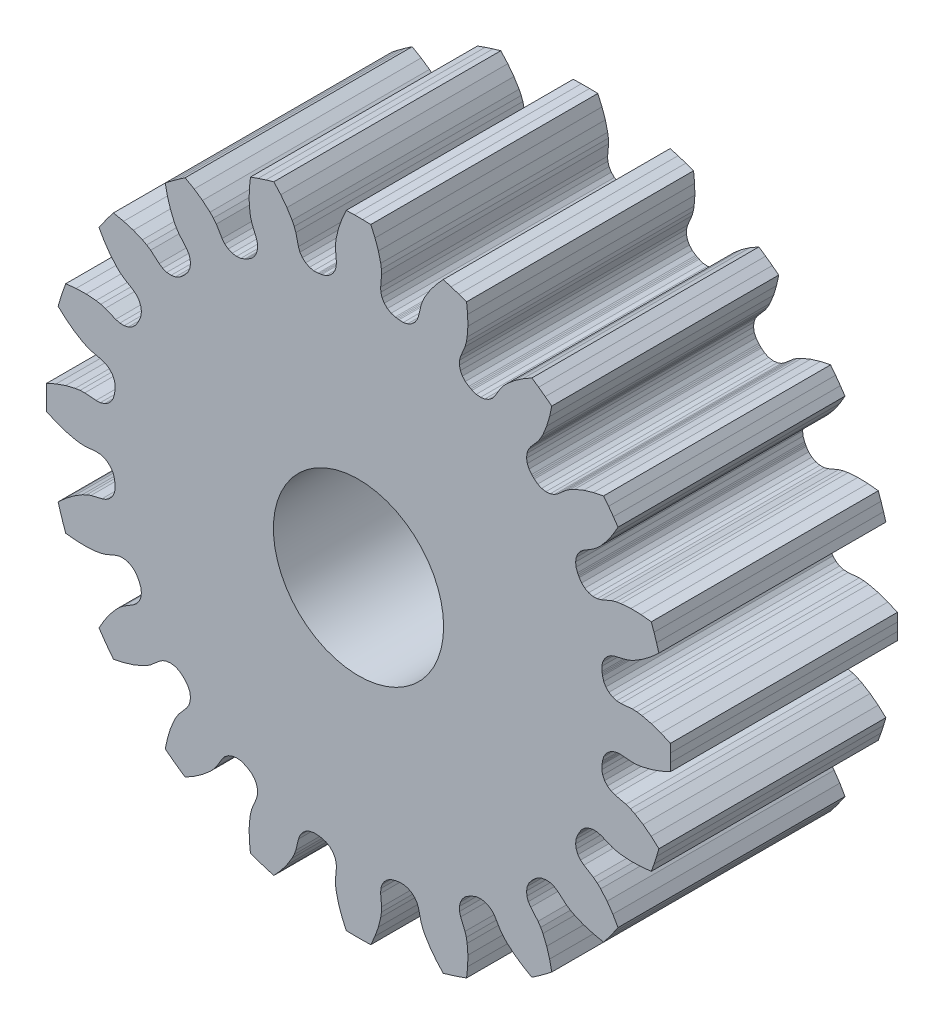
SolidWorks part; units mm, degrees
material "ABS"
ref_plane "Спереди" through (0, 0, 0) normal (0, 0, 1) x (1, 0, 0)
ref_plane "Сверху" through (0, 0, 0) normal (0, 1, 0) x (1, 0, 0)
ref_plane "Справа" through (0, 0, 0) normal (1, 0, 0) x (0, 0, -1)
ref_plane "Плоскость1" through (0, 0, 4) normal (0, 0, 1) x (1, 0, 0)
sketch "Эскиз1" plane through (0, 0, 4) normal (0, 0, 1) x (1, 0, 0)
  line L0 (1.1137, -1.1137) -> (0.982, -1.2314)
  line L1 (0.982, -1.2314) -> (0.838, -1.3336)
  line L2 (0.838, -1.3336) -> (0.6834, -1.419)
  line L3 (0.6834, -1.419) -> (0.5202, -1.4866)
  line L4 (0.5202, -1.4866) -> (0.3505, -1.5355)
  line L5 (0.3505, -1.5355) -> (0.1763, -1.5651)
  line L6 (0.1763, -1.5651) -> (0, -1.575)
  line L7 (0, -1.575) -> (-0.1763, -1.5651)
  line L8 (-0.1763, -1.5651) -> (-0.3505, -1.5355)
  line L9 (-0.3505, -1.5355) -> (-0.5202, -1.4866)
  line L10 (-0.5202, -1.4866) -> (-0.6834, -1.419)
  line L11 (-0.6834, -1.419) -> (-0.838, -1.3336)
  line L12 (-0.838, -1.3336) -> (-0.982, -1.2314)
  line L13 (-0.982, -1.2314) -> (-1.1137, -1.1137)
  line L14 (-1.1137, -1.1137) -> (-1.2314, -0.982)
  line L15 (-1.2314, -0.982) -> (-1.3336, -0.838)
  line L16 (-1.3336, -0.838) -> (-1.419, -0.6834)
  line L17 (-1.419, -0.6834) -> (-1.4866, -0.5202)
  line L18 (-1.4866, -0.5202) -> (-1.5355, -0.3505)
  line L19 (-1.5355, -0.3505) -> (-1.5651, -0.1763)
  line L20 (-1.5651, -0.1763) -> (-1.575, 0)
  line L21 (-1.575, 0) -> (-1.5651, 0.1763)
  line L22 (-1.5651, 0.1763) -> (-1.5355, 0.3505)
  line L23 (-1.5355, 0.3505) -> (-1.4866, 0.5202)
  line L24 (-1.4866, 0.5202) -> (-1.419, 0.6834)
  line L25 (-1.419, 0.6834) -> (-1.3336, 0.838)
  line L26 (-1.3336, 0.838) -> (-1.2314, 0.982)
  line L27 (-1.2314, 0.982) -> (-1.1137, 1.1137)
  line L28 (-1.1137, 1.1137) -> (-0.982, 1.2314)
  line L29 (-0.982, 1.2314) -> (-0.838, 1.3336)
  line L30 (-0.838, 1.3336) -> (-0.6834, 1.419)
  line L31 (-0.6834, 1.419) -> (-0.5202, 1.4866)
  line L32 (-0.5202, 1.4866) -> (-0.3505, 1.5355)
  line L33 (-0.3505, 1.5355) -> (-0.1763, 1.5651)
  line L34 (-0.1763, 1.5651) -> (0, 1.575)
  line L35 (0, 1.575) -> (0.1763, 1.5651)
  line L36 (0.1763, 1.5651) -> (0.3505, 1.5355)
  line L37 (0.3505, 1.5355) -> (0.5202, 1.4866)
  line L38 (0.5202, 1.4866) -> (0.6834, 1.419)
  line L39 (0.6834, 1.419) -> (0.838, 1.3336)
  line L40 (0.838, 1.3336) -> (0.982, 1.2314)
  line L41 (0.982, 1.2314) -> (1.1137, 1.1137)
  line L42 (1.1137, 1.1137) -> (1.2314, 0.982)
  line L43 (1.2314, 0.982) -> (1.3336, 0.838)
  line L44 (1.3336, 0.838) -> (1.419, 0.6834)
  line L45 (1.419, 0.6834) -> (1.4866, 0.5202)
  line L46 (1.4866, 0.5202) -> (1.5355, 0.3505)
  line L47 (1.5355, 0.3505) -> (1.5651, 0.1763)
  line L48 (1.5651, 0.1763) -> (1.575, 0)
  line L49 (1.575, 0) -> (1.5651, -0.1763)
  line L50 (1.5651, -0.1763) -> (1.5355, -0.3505)
  line L51 (1.5355, -0.3505) -> (1.4866, -0.5202)
  line L52 (1.4866, -0.5202) -> (1.419, -0.6834)
  line L53 (1.419, -0.6834) -> (1.3336, -0.838)
  line L54 (1.3336, -0.838) -> (1.2314, -0.982)
  line L55 (1.2314, -0.982) -> (1.1137, -1.1137)
  line L56 (4.3213, -0.5748) -> (4.3594, -0.5091)
  line L57 (4.3594, -0.5091) -> (4.4126, -0.4548)
  line L58 (4.4126, -0.4548) -> (4.4776, -0.4155)
  line L59 (4.4776, -0.4155) -> (4.5504, -0.3935)
  line L60 (4.5504, -0.3935) -> (4.6263, -0.3903)
  line L61 (4.6263, -0.3903) -> (4.8236, -0.4066)
  line L62 (4.8236, -0.4066) -> (4.9072, -0.4032)
  line L63 (4.9072, -0.4032) -> (4.9912, -0.3911)
  line L64 (4.9912, -0.3911) -> (5.1598, -0.35)
  line L65 (5.1598, -0.35) -> (5.3282, -0.2909)
  line L66 (5.3282, -0.2909) -> (5.4957, -0.2164)
  line L67 (5.4957, -0.2164) -> (5.4995, -0.0722)
  line L68 (5.4995, -0.0722) -> (5.4995, 0.0722)
  line L69 (5.4995, 0.0722) -> (5.4957, 0.2164)
  line L70 (5.4957, 0.2164) -> (5.3282, 0.2909)
  line L71 (5.3282, 0.2909) -> (5.1598, 0.35)
  line L72 (5.1598, 0.35) -> (4.9912, 0.3911)
  line L73 (4.9912, 0.3911) -> (4.9072, 0.4032)
  line L74 (4.9072, 0.4032) -> (4.8236, 0.4066)
  line L75 (4.8236, 0.4066) -> (4.6263, 0.3903)
  line L76 (4.6263, 0.3903) -> (4.5504, 0.3935)
  line L77 (4.5504, 0.3935) -> (4.4776, 0.4155)
  line L78 (4.4776, 0.4155) -> (4.4126, 0.4548)
  line L79 (4.4126, 0.4548) -> (4.3594, 0.5091)
  line L80 (4.3594, 0.5091) -> (4.3213, 0.5748)
  line L81 (4.3213, 0.5748) -> (4.3007, 0.6479)
  line L82 (4.3007, 0.6479) -> (4.2974, 0.6696)
  line L83 (4.2974, 0.6696) -> (4.2939, 0.6912)
  line L84 (4.2939, 0.6912) -> (4.2904, 0.7128)
  line L85 (4.2904, 0.7128) -> (4.2874, 0.7887)
  line L86 (4.2874, 0.7887) -> (4.3033, 0.863)
  line L87 (4.3033, 0.863) -> (4.3372, 0.931)
  line L88 (4.3372, 0.931) -> (4.3869, 0.9885)
  line L89 (4.3869, 0.9885) -> (4.4493, 1.0319)
  line L90 (4.4493, 1.0319) -> (4.5205, 1.0585)
  line L91 (4.5205, 1.0585) -> (4.7132, 1.1039)
  line L92 (4.7132, 1.1039) -> (4.7916, 1.133)
  line L93 (4.7916, 1.133) -> (4.8678, 1.1704)
  line L94 (4.8678, 1.1704) -> (5.0154, 1.2616)
  line L95 (5.0154, 1.2616) -> (5.1573, 1.3698)
  line L96 (5.1573, 1.3698) -> (5.2936, 1.4925)
  line L97 (5.2936, 1.4925) -> (5.2527, 1.6308)
  line L98 (5.2527, 1.6308) -> (5.2081, 1.7681)
  line L99 (5.2081, 1.7681) -> (5.1599, 1.9041)
  line L100 (5.1599, 1.9041) -> (4.9775, 1.9232)
  line L101 (4.9775, 1.9232) -> (4.7991, 1.9273)
  line L102 (4.7991, 1.9273) -> (4.6261, 1.9143)
  line L103 (4.6261, 1.9143) -> (4.5424, 1.8998)
  line L104 (4.5424, 1.8998) -> (4.4619, 1.8772)
  line L105 (4.4619, 1.8772) -> (4.2793, 1.8008)
  line L106 (4.2793, 1.8008) -> (4.2061, 1.7804)
  line L107 (4.2061, 1.7804) -> (4.1301, 1.7788)
  line L108 (4.1301, 1.7788) -> (4.0561, 1.7961)
  line L109 (4.0561, 1.7961) -> (3.9887, 1.8313)
  line L110 (3.9887, 1.8313) -> (3.9322, 1.882)
  line L111 (3.9322, 1.882) -> (3.89, 1.9452)
  line L112 (3.89, 1.9452) -> (3.8801, 1.9647)
  line L113 (3.8801, 1.9647) -> (3.8702, 1.9842)
  line L114 (3.8702, 1.9842) -> (3.8602, 2.0037)
  line L115 (3.8602, 2.0037) -> (3.8339, 2.075)
  line L116 (3.8339, 2.075) -> (3.826, 2.1506)
  line L117 (3.826, 2.1506) -> (3.8372, 2.2257)
  line L118 (3.8372, 2.2257) -> (3.8667, 2.2958)
  line L119 (3.8667, 2.2958) -> (3.9126, 2.3563)
  line L120 (3.9126, 2.3563) -> (3.9721, 2.4036)
  line L121 (3.9721, 2.4036) -> (4.1414, 2.5064)
  line L122 (4.1414, 2.5064) -> (4.207, 2.5582)
  line L123 (4.207, 2.5582) -> (4.2679, 2.6174)
  line L124 (4.2679, 2.6174) -> (4.3801, 2.7497)
  line L125 (4.3801, 2.7497) -> (4.4816, 2.8965)
  line L126 (4.4816, 2.8965) -> (4.5734, 3.0552)
  line L127 (4.5734, 3.0552) -> (4.4916, 3.1742)
  line L128 (4.4916, 3.1742) -> (4.4068, 3.2909)
  line L129 (4.4068, 3.2909) -> (4.3189, 3.4054)
  line L130 (4.3189, 3.4054) -> (4.1396, 3.3672)
  line L131 (4.1396, 3.3672) -> (3.9686, 3.316)
  line L132 (3.9686, 3.316) -> (3.8081, 3.2502)
  line L133 (3.8081, 3.2502) -> (3.733, 3.2105)
  line L134 (3.733, 3.2105) -> (3.6634, 3.1642)
  line L135 (3.6634, 3.1642) -> (3.5134, 3.035)
  line L136 (3.5134, 3.035) -> (3.45, 2.993)
  line L137 (3.45, 2.993) -> (3.3783, 2.968)
  line L138 (3.3783, 2.968) -> (3.3026, 2.9616)
  line L139 (3.3026, 2.9616) -> (3.2276, 2.9742)
  line L140 (3.2276, 2.9742) -> (3.1581, 3.005)
  line L141 (3.1581, 3.005) -> (3.0985, 3.0521)
  line L142 (3.0985, 3.0521) -> (3.0831, 3.0676)
  line L143 (3.0831, 3.0676) -> (3.0676, 3.0831)
  line L144 (3.0676, 3.0831) -> (3.0521, 3.0985)
  line L145 (3.0521, 3.0985) -> (3.005, 3.1581)
  line L146 (3.005, 3.1581) -> (2.9742, 3.2276)
  line L147 (2.9742, 3.2276) -> (2.9616, 3.3026)
  line L148 (2.9616, 3.3026) -> (2.968, 3.3783)
  line L149 (2.968, 3.3783) -> (2.993, 3.45)
  line L150 (2.993, 3.45) -> (3.035, 3.5134)
  line L151 (3.035, 3.5134) -> (3.1642, 3.6634)
  line L152 (3.1642, 3.6634) -> (3.2105, 3.733)
  line L153 (3.2105, 3.733) -> (3.2502, 3.8081)
  line L154 (3.2502, 3.8081) -> (3.316, 3.9686)
  line L155 (3.316, 3.9686) -> (3.3672, 4.1396)
  line L156 (3.3672, 4.1396) -> (3.4054, 4.3189)
  line L157 (3.4054, 4.3189) -> (3.2909, 4.4068)
  line L158 (3.2909, 4.4068) -> (3.1742, 4.4916)
  line L159 (3.1742, 4.4916) -> (3.0552, 4.5734)
  line L160 (3.0552, 4.5734) -> (2.8965, 4.4816)
  line L161 (2.8965, 4.4816) -> (2.7497, 4.3801)
  line L162 (2.7497, 4.3801) -> (2.6174, 4.2679)
  line L163 (2.6174, 4.2679) -> (2.5582, 4.207)
  line L164 (2.5582, 4.207) -> (2.5064, 4.1414)
  line L165 (2.5064, 4.1414) -> (2.4036, 3.9721)
  line L166 (2.4036, 3.9721) -> (2.3563, 3.9126)
  line L167 (2.3563, 3.9126) -> (2.2958, 3.8667)
  line L168 (2.2958, 3.8667) -> (2.2257, 3.8372)
  line L169 (2.2257, 3.8372) -> (2.1506, 3.826)
  line L170 (2.1506, 3.826) -> (2.075, 3.8339)
  line L171 (2.075, 3.8339) -> (2.0037, 3.8602)
  line L172 (2.0037, 3.8602) -> (1.9842, 3.8702)
  line L173 (1.9842, 3.8702) -> (1.9647, 3.8801)
  line L174 (1.9647, 3.8801) -> (1.9452, 3.89)
  line L175 (1.9452, 3.89) -> (1.882, 3.9322)
  line L176 (1.882, 3.9322) -> (1.8313, 3.9887)
  line L177 (1.8313, 3.9887) -> (1.7961, 4.0561)
  line L178 (1.7961, 4.0561) -> (1.7788, 4.1301)
  line L179 (1.7788, 4.1301) -> (1.7804, 4.2061)
  line L180 (1.7804, 4.2061) -> (1.8008, 4.2793)
  line L181 (1.8008, 4.2793) -> (1.8772, 4.4619)
  line L182 (1.8772, 4.4619) -> (1.8998, 4.5424)
  line L183 (1.8998, 4.5424) -> (1.9143, 4.6261)
  line L184 (1.9143, 4.6261) -> (1.9273, 4.7991)
  line L185 (1.9273, 4.7991) -> (1.9232, 4.9775)
  line L186 (1.9232, 4.9775) -> (1.9041, 5.1599)
  line L187 (1.9041, 5.1599) -> (1.7681, 5.2081)
  line L188 (1.7681, 5.2081) -> (1.6308, 5.2527)
  line L189 (1.6308, 5.2527) -> (1.4925, 5.2936)
  line L190 (1.4925, 5.2936) -> (1.3698, 5.1573)
  line L191 (1.3698, 5.1573) -> (1.2616, 5.0154)
  line L192 (1.2616, 5.0154) -> (1.1704, 4.8678)
  line L193 (1.1704, 4.8678) -> (1.133, 4.7916)
  line L194 (1.133, 4.7916) -> (1.1039, 4.7132)
  line L195 (1.1039, 4.7132) -> (1.0585, 4.5205)
  line L196 (1.0585, 4.5205) -> (1.0319, 4.4493)
  line L197 (1.0319, 4.4493) -> (0.9885, 4.3869)
  line L198 (0.9885, 4.3869) -> (0.931, 4.3372)
  line L199 (0.931, 4.3372) -> (0.863, 4.3033)
  line L200 (0.863, 4.3033) -> (0.7887, 4.2874)
  line L201 (0.7887, 4.2874) -> (0.7128, 4.2904)
  line L202 (0.7128, 4.2904) -> (0.6912, 4.2939)
  line L203 (0.6912, 4.2939) -> (0.6696, 4.2974)
  line L204 (0.6696, 4.2974) -> (0.6479, 4.3007)
  line L205 (0.6479, 4.3007) -> (0.5748, 4.3213)
  line L206 (0.5748, 4.3213) -> (0.5091, 4.3594)
  line L207 (0.5091, 4.3594) -> (0.4548, 4.4126)
  line L208 (0.4548, 4.4126) -> (0.4155, 4.4776)
  line L209 (0.4155, 4.4776) -> (0.3935, 4.5504)
  line L210 (0.3935, 4.5504) -> (0.3903, 4.6263)
  line L211 (0.3903, 4.6263) -> (0.4066, 4.8236)
  line L212 (0.4066, 4.8236) -> (0.4032, 4.9072)
  line L213 (0.4032, 4.9072) -> (0.3911, 4.9912)
  line L214 (0.3911, 4.9912) -> (0.35, 5.1598)
  line L215 (0.35, 5.1598) -> (0.2909, 5.3282)
  line L216 (0.2909, 5.3282) -> (0.2164, 5.4957)
  line L217 (0.2164, 5.4957) -> (0.0722, 5.4995)
  line L218 (0.0722, 5.4995) -> (-0.0722, 5.4995)
  line L219 (-0.0722, 5.4995) -> (-0.2164, 5.4957)
  line L220 (-0.2164, 5.4957) -> (-0.2909, 5.3282)
  line L221 (-0.2909, 5.3282) -> (-0.35, 5.1598)
  line L222 (-0.35, 5.1598) -> (-0.3911, 4.9912)
  line L223 (-0.3911, 4.9912) -> (-0.4032, 4.9072)
  line L224 (-0.4032, 4.9072) -> (-0.4066, 4.8236)
  line L225 (-0.4066, 4.8236) -> (-0.3903, 4.6263)
  line L226 (-0.3903, 4.6263) -> (-0.3935, 4.5504)
  line L227 (-0.3935, 4.5504) -> (-0.4155, 4.4776)
  line L228 (-0.4155, 4.4776) -> (-0.4548, 4.4126)
  line L229 (-0.4548, 4.4126) -> (-0.5091, 4.3594)
  line L230 (-0.5091, 4.3594) -> (-0.5748, 4.3213)
  line L231 (-0.5748, 4.3213) -> (-0.6479, 4.3007)
  line L232 (-0.6479, 4.3007) -> (-0.6696, 4.2974)
  line L233 (-0.6696, 4.2974) -> (-0.6912, 4.2939)
  line L234 (-0.6912, 4.2939) -> (-0.7128, 4.2904)
  line L235 (-0.7128, 4.2904) -> (-0.7887, 4.2874)
  line L236 (-0.7887, 4.2874) -> (-0.863, 4.3033)
  line L237 (-0.863, 4.3033) -> (-0.931, 4.3372)
  line L238 (-0.931, 4.3372) -> (-0.9885, 4.3869)
  line L239 (-0.9885, 4.3869) -> (-1.0319, 4.4493)
  line L240 (-1.0319, 4.4493) -> (-1.0585, 4.5205)
  line L241 (-1.0585, 4.5205) -> (-1.1039, 4.7132)
  line L242 (-1.1039, 4.7132) -> (-1.133, 4.7916)
  line L243 (-1.133, 4.7916) -> (-1.1704, 4.8678)
  line L244 (-1.1704, 4.8678) -> (-1.2616, 5.0154)
  line L245 (-1.2616, 5.0154) -> (-1.3698, 5.1573)
  line L246 (-1.3698, 5.1573) -> (-1.4925, 5.2936)
  line L247 (-1.4925, 5.2936) -> (-1.6308, 5.2527)
  line L248 (-1.6308, 5.2527) -> (-1.7681, 5.2081)
  line L249 (-1.7681, 5.2081) -> (-1.9041, 5.1599)
  line L250 (-1.9041, 5.1599) -> (-1.9232, 4.9775)
  line L251 (-1.9232, 4.9775) -> (-1.9273, 4.7991)
  line L252 (-1.9273, 4.7991) -> (-1.9143, 4.6261)
  line L253 (-1.9143, 4.6261) -> (-1.8998, 4.5424)
  line L254 (-1.8998, 4.5424) -> (-1.8772, 4.4619)
  line L255 (-1.8772, 4.4619) -> (-1.8008, 4.2793)
  line L256 (-1.8008, 4.2793) -> (-1.7804, 4.2061)
  line L257 (-1.7804, 4.2061) -> (-1.7788, 4.1301)
  line L258 (-1.7788, 4.1301) -> (-1.7961, 4.0561)
  line L259 (-1.7961, 4.0561) -> (-1.8313, 3.9887)
  line L260 (-1.8313, 3.9887) -> (-1.882, 3.9322)
  line L261 (-1.882, 3.9322) -> (-1.9452, 3.89)
  line L262 (-1.9452, 3.89) -> (-1.9647, 3.8801)
  line L263 (-1.9647, 3.8801) -> (-1.9842, 3.8702)
  line L264 (-1.9842, 3.8702) -> (-2.0037, 3.8602)
  line L265 (-2.0037, 3.8602) -> (-2.075, 3.8339)
  line L266 (-2.075, 3.8339) -> (-2.1506, 3.826)
  line L267 (-2.1506, 3.826) -> (-2.2257, 3.8372)
  line L268 (-2.2257, 3.8372) -> (-2.2958, 3.8667)
  line L269 (-2.2958, 3.8667) -> (-2.3563, 3.9126)
  line L270 (-2.3563, 3.9126) -> (-2.4036, 3.9721)
  line L271 (-2.4036, 3.9721) -> (-2.5064, 4.1414)
  line L272 (-2.5064, 4.1414) -> (-2.5582, 4.207)
  line L273 (-2.5582, 4.207) -> (-2.6174, 4.2679)
  line L274 (-2.6174, 4.2679) -> (-2.7497, 4.3801)
  line L275 (-2.7497, 4.3801) -> (-2.8965, 4.4816)
  line L276 (-2.8965, 4.4816) -> (-3.0552, 4.5734)
  line L277 (-3.0552, 4.5734) -> (-3.1742, 4.4916)
  line L278 (-3.1742, 4.4916) -> (-3.2909, 4.4068)
  line L279 (-3.2909, 4.4068) -> (-3.4054, 4.3189)
  line L280 (-3.4054, 4.3189) -> (-3.3672, 4.1396)
  line L281 (-3.3672, 4.1396) -> (-3.316, 3.9686)
  line L282 (-3.316, 3.9686) -> (-3.2502, 3.8081)
  line L283 (-3.2502, 3.8081) -> (-3.2105, 3.733)
  line L284 (-3.2105, 3.733) -> (-3.1642, 3.6634)
  line L285 (-3.1642, 3.6634) -> (-3.035, 3.5134)
  line L286 (-3.035, 3.5134) -> (-2.993, 3.45)
  line L287 (-2.993, 3.45) -> (-2.968, 3.3783)
  line L288 (-2.968, 3.3783) -> (-2.9616, 3.3026)
  line L289 (-2.9616, 3.3026) -> (-2.9742, 3.2276)
  line L290 (-2.9742, 3.2276) -> (-3.005, 3.1581)
  line L291 (-3.005, 3.1581) -> (-3.0521, 3.0985)
  line L292 (-3.0521, 3.0985) -> (-3.0676, 3.0831)
  line L293 (-3.0676, 3.0831) -> (-3.0831, 3.0676)
  line L294 (-3.0831, 3.0676) -> (-3.0985, 3.0521)
  line L295 (-3.0985, 3.0521) -> (-3.1581, 3.005)
  line L296 (-3.1581, 3.005) -> (-3.2276, 2.9742)
  line L297 (-3.2276, 2.9742) -> (-3.3026, 2.9616)
  line L298 (-3.3026, 2.9616) -> (-3.3783, 2.968)
  line L299 (-3.3783, 2.968) -> (-3.45, 2.993)
  line L300 (-3.45, 2.993) -> (-3.5134, 3.035)
  line L301 (-3.5134, 3.035) -> (-3.6634, 3.1642)
  line L302 (-3.6634, 3.1642) -> (-3.733, 3.2105)
  line L303 (-3.733, 3.2105) -> (-3.8081, 3.2502)
  line L304 (-3.8081, 3.2502) -> (-3.9686, 3.316)
  line L305 (-3.9686, 3.316) -> (-4.1396, 3.3672)
  line L306 (-4.1396, 3.3672) -> (-4.3189, 3.4054)
  line L307 (-4.3189, 3.4054) -> (-4.4068, 3.2909)
  line L308 (-4.4068, 3.2909) -> (-4.4916, 3.1742)
  line L309 (-4.4916, 3.1742) -> (-4.5734, 3.0552)
  line L310 (-4.5734, 3.0552) -> (-4.4816, 2.8965)
  line L311 (-4.4816, 2.8965) -> (-4.3801, 2.7497)
  line L312 (-4.3801, 2.7497) -> (-4.2679, 2.6174)
  line L313 (-4.2679, 2.6174) -> (-4.207, 2.5582)
  line L314 (-4.207, 2.5582) -> (-4.1414, 2.5064)
  line L315 (-4.1414, 2.5064) -> (-3.9721, 2.4036)
  line L316 (-3.9721, 2.4036) -> (-3.9126, 2.3563)
  line L317 (-3.9126, 2.3563) -> (-3.8667, 2.2958)
  line L318 (-3.8667, 2.2958) -> (-3.8372, 2.2257)
  line L319 (-3.8372, 2.2257) -> (-3.826, 2.1506)
  line L320 (-3.826, 2.1506) -> (-3.8339, 2.075)
  line L321 (-3.8339, 2.075) -> (-3.8602, 2.0037)
  line L322 (-3.8602, 2.0037) -> (-3.8702, 1.9842)
  line L323 (-3.8702, 1.9842) -> (-3.8801, 1.9647)
  line L324 (-3.8801, 1.9647) -> (-3.89, 1.9452)
  line L325 (-3.89, 1.9452) -> (-3.9322, 1.882)
  line L326 (-3.9322, 1.882) -> (-3.9887, 1.8313)
  line L327 (-3.9887, 1.8313) -> (-4.0561, 1.7961)
  line L328 (-4.0561, 1.7961) -> (-4.1301, 1.7788)
  line L329 (-4.1301, 1.7788) -> (-4.2061, 1.7804)
  line L330 (-4.2061, 1.7804) -> (-4.2793, 1.8008)
  line L331 (-4.2793, 1.8008) -> (-4.4619, 1.8772)
  line L332 (-4.4619, 1.8772) -> (-4.5424, 1.8998)
  line L333 (-4.5424, 1.8998) -> (-4.6261, 1.9143)
  line L334 (-4.6261, 1.9143) -> (-4.7991, 1.9273)
  line L335 (-4.7991, 1.9273) -> (-4.9775, 1.9232)
  line L336 (-4.9775, 1.9232) -> (-5.1599, 1.9041)
  line L337 (-5.1599, 1.9041) -> (-5.2081, 1.7681)
  line L338 (-5.2081, 1.7681) -> (-5.2527, 1.6308)
  line L339 (-5.2527, 1.6308) -> (-5.2936, 1.4925)
  line L340 (-5.2936, 1.4925) -> (-5.1573, 1.3698)
  line L341 (-5.1573, 1.3698) -> (-5.0154, 1.2616)
  line L342 (-5.0154, 1.2616) -> (-4.8678, 1.1704)
  line L343 (-4.8678, 1.1704) -> (-4.7916, 1.133)
  line L344 (-4.7916, 1.133) -> (-4.7132, 1.1039)
  line L345 (-4.7132, 1.1039) -> (-4.5205, 1.0585)
  line L346 (-4.5205, 1.0585) -> (-4.4493, 1.0319)
  line L347 (-4.4493, 1.0319) -> (-4.3869, 0.9885)
  line L348 (-4.3869, 0.9885) -> (-4.3372, 0.931)
  line L349 (-4.3372, 0.931) -> (-4.3033, 0.863)
  line L350 (-4.3033, 0.863) -> (-4.2874, 0.7887)
  line L351 (-4.2874, 0.7887) -> (-4.2904, 0.7128)
  line L352 (-4.2904, 0.7128) -> (-4.2939, 0.6912)
  line L353 (-4.2939, 0.6912) -> (-4.2974, 0.6696)
  line L354 (-4.2974, 0.6696) -> (-4.3007, 0.6479)
  line L355 (-4.3007, 0.6479) -> (-4.3213, 0.5748)
  line L356 (-4.3213, 0.5748) -> (-4.3594, 0.5091)
  line L357 (-4.3594, 0.5091) -> (-4.4126, 0.4548)
  line L358 (-4.4126, 0.4548) -> (-4.4776, 0.4155)
  line L359 (-4.4776, 0.4155) -> (-4.5504, 0.3935)
  line L360 (-4.5504, 0.3935) -> (-4.6263, 0.3903)
  line L361 (-4.6263, 0.3903) -> (-4.8236, 0.4066)
  line L362 (-4.8236, 0.4066) -> (-4.9072, 0.4032)
  line L363 (-4.9072, 0.4032) -> (-4.9912, 0.3911)
  line L364 (-4.9912, 0.3911) -> (-5.1598, 0.35)
  line L365 (-5.1598, 0.35) -> (-5.3282, 0.2909)
  line L366 (-5.3282, 0.2909) -> (-5.4957, 0.2164)
  line L367 (-5.4957, 0.2164) -> (-5.4995, 0.0722)
  line L368 (-5.4995, 0.0722) -> (-5.4995, -0.0722)
  line L369 (-5.4995, -0.0722) -> (-5.4957, -0.2164)
  line L370 (-5.4957, -0.2164) -> (-5.3282, -0.2909)
  line L371 (-5.3282, -0.2909) -> (-5.1598, -0.35)
  line L372 (-5.1598, -0.35) -> (-4.9912, -0.3911)
  line L373 (-4.9912, -0.3911) -> (-4.9072, -0.4032)
  line L374 (-4.9072, -0.4032) -> (-4.8236, -0.4066)
  line L375 (-4.8236, -0.4066) -> (-4.6263, -0.3903)
  line L376 (-4.6263, -0.3903) -> (-4.5504, -0.3935)
  line L377 (-4.5504, -0.3935) -> (-4.4776, -0.4155)
  line L378 (-4.4776, -0.4155) -> (-4.4126, -0.4548)
  line L379 (-4.4126, -0.4548) -> (-4.3594, -0.5091)
  line L380 (-4.3594, -0.5091) -> (-4.3213, -0.5748)
  line L381 (-4.3213, -0.5748) -> (-4.3007, -0.6479)
  line L382 (-4.3007, -0.6479) -> (-4.2974, -0.6696)
  line L383 (-4.2974, -0.6696) -> (-4.2939, -0.6912)
  line L384 (-4.2939, -0.6912) -> (-4.2904, -0.7128)
  line L385 (-4.2904, -0.7128) -> (-4.2874, -0.7887)
  line L386 (-4.2874, -0.7887) -> (-4.3033, -0.863)
  line L387 (-4.3033, -0.863) -> (-4.3372, -0.931)
  line L388 (-4.3372, -0.931) -> (-4.3869, -0.9885)
  line L389 (-4.3869, -0.9885) -> (-4.4493, -1.0319)
  line L390 (-4.4493, -1.0319) -> (-4.5205, -1.0585)
  line L391 (-4.5205, -1.0585) -> (-4.7132, -1.1039)
  line L392 (-4.7132, -1.1039) -> (-4.7916, -1.133)
  line L393 (-4.7916, -1.133) -> (-4.8678, -1.1704)
  line L394 (-4.8678, -1.1704) -> (-5.0154, -1.2616)
  line L395 (-5.0154, -1.2616) -> (-5.1573, -1.3698)
  line L396 (-5.1573, -1.3698) -> (-5.2936, -1.4925)
  line L397 (-5.2936, -1.4925) -> (-5.2527, -1.6308)
  line L398 (-5.2527, -1.6308) -> (-5.2081, -1.7681)
  line L399 (-5.2081, -1.7681) -> (-5.1599, -1.9041)
  line L400 (-5.1599, -1.9041) -> (-4.9775, -1.9232)
  line L401 (-4.9775, -1.9232) -> (-4.7991, -1.9273)
  line L402 (-4.7991, -1.9273) -> (-4.6261, -1.9143)
  line L403 (-4.6261, -1.9143) -> (-4.5424, -1.8998)
  line L404 (-4.5424, -1.8998) -> (-4.4619, -1.8772)
  line L405 (-4.4619, -1.8772) -> (-4.2793, -1.8008)
  line L406 (-4.2793, -1.8008) -> (-4.2061, -1.7804)
  line L407 (-4.2061, -1.7804) -> (-4.1301, -1.7788)
  line L408 (-4.1301, -1.7788) -> (-4.0561, -1.7961)
  line L409 (-4.0561, -1.7961) -> (-3.9887, -1.8313)
  line L410 (-3.9887, -1.8313) -> (-3.9322, -1.882)
  line L411 (-3.9322, -1.882) -> (-3.89, -1.9452)
  line L412 (-3.89, -1.9452) -> (-3.8801, -1.9647)
  line L413 (-3.8801, -1.9647) -> (-3.8702, -1.9842)
  line L414 (-3.8702, -1.9842) -> (-3.8602, -2.0037)
  line L415 (-3.8602, -2.0037) -> (-3.8339, -2.075)
  line L416 (-3.8339, -2.075) -> (-3.826, -2.1506)
  line L417 (-3.826, -2.1506) -> (-3.8372, -2.2257)
  line L418 (-3.8372, -2.2257) -> (-3.8667, -2.2958)
  line L419 (-3.8667, -2.2958) -> (-3.9126, -2.3563)
  line L420 (-3.9126, -2.3563) -> (-3.9721, -2.4036)
  line L421 (-3.9721, -2.4036) -> (-4.1414, -2.5064)
  line L422 (-4.1414, -2.5064) -> (-4.207, -2.5582)
  line L423 (-4.207, -2.5582) -> (-4.2679, -2.6174)
  line L424 (-4.2679, -2.6174) -> (-4.3801, -2.7497)
  line L425 (-4.3801, -2.7497) -> (-4.4816, -2.8965)
  line L426 (-4.4816, -2.8965) -> (-4.5734, -3.0552)
  line L427 (-4.5734, -3.0552) -> (-4.4916, -3.1742)
  line L428 (-4.4916, -3.1742) -> (-4.4068, -3.2909)
  line L429 (-4.4068, -3.2909) -> (-4.3189, -3.4054)
  line L430 (-4.3189, -3.4054) -> (-4.1396, -3.3672)
  line L431 (-4.1396, -3.3672) -> (-3.9686, -3.316)
  line L432 (-3.9686, -3.316) -> (-3.8081, -3.2502)
  line L433 (-3.8081, -3.2502) -> (-3.733, -3.2105)
  line L434 (-3.733, -3.2105) -> (-3.6634, -3.1642)
  line L435 (-3.6634, -3.1642) -> (-3.5134, -3.035)
  line L436 (-3.5134, -3.035) -> (-3.45, -2.993)
  line L437 (-3.45, -2.993) -> (-3.3783, -2.968)
  line L438 (-3.3783, -2.968) -> (-3.3026, -2.9616)
  line L439 (-3.3026, -2.9616) -> (-3.2276, -2.9742)
  line L440 (-3.2276, -2.9742) -> (-3.1581, -3.005)
  line L441 (-3.1581, -3.005) -> (-3.0985, -3.0521)
  line L442 (-3.0985, -3.0521) -> (-3.0831, -3.0676)
  line L443 (-3.0831, -3.0676) -> (-3.0676, -3.0831)
  line L444 (-3.0676, -3.0831) -> (-3.0521, -3.0985)
  line L445 (-3.0521, -3.0985) -> (-3.005, -3.1581)
  line L446 (-3.005, -3.1581) -> (-2.9742, -3.2276)
  line L447 (-2.9742, -3.2276) -> (-2.9616, -3.3026)
  line L448 (-2.9616, -3.3026) -> (-2.968, -3.3783)
  line L449 (-2.968, -3.3783) -> (-2.993, -3.45)
  line L450 (-2.993, -3.45) -> (-3.035, -3.5134)
  line L451 (-3.035, -3.5134) -> (-3.1642, -3.6634)
  line L452 (-3.1642, -3.6634) -> (-3.2105, -3.733)
  line L453 (-3.2105, -3.733) -> (-3.2502, -3.8081)
  line L454 (-3.2502, -3.8081) -> (-3.316, -3.9686)
  line L455 (-3.316, -3.9686) -> (-3.3672, -4.1396)
  line L456 (-3.3672, -4.1396) -> (-3.4054, -4.3189)
  line L457 (-3.4054, -4.3189) -> (-3.2909, -4.4068)
  line L458 (-3.2909, -4.4068) -> (-3.1742, -4.4916)
  line L459 (-3.1742, -4.4916) -> (-3.0552, -4.5734)
  line L460 (-3.0552, -4.5734) -> (-2.8965, -4.4816)
  line L461 (-2.8965, -4.4816) -> (-2.7497, -4.3801)
  line L462 (-2.7497, -4.3801) -> (-2.6174, -4.2679)
  line L463 (-2.6174, -4.2679) -> (-2.5582, -4.207)
  line L464 (-2.5582, -4.207) -> (-2.5064, -4.1414)
  line L465 (-2.5064, -4.1414) -> (-2.4036, -3.9721)
  line L466 (-2.4036, -3.9721) -> (-2.3563, -3.9126)
  line L467 (-2.3563, -3.9126) -> (-2.2958, -3.8667)
  line L468 (-2.2958, -3.8667) -> (-2.2257, -3.8372)
  line L469 (-2.2257, -3.8372) -> (-2.1506, -3.826)
  line L470 (-2.1506, -3.826) -> (-2.075, -3.8339)
  line L471 (-2.075, -3.8339) -> (-2.0037, -3.8602)
  line L472 (-2.0037, -3.8602) -> (-1.9842, -3.8702)
  line L473 (-1.9842, -3.8702) -> (-1.9647, -3.8801)
  line L474 (-1.9647, -3.8801) -> (-1.9452, -3.89)
  line L475 (-1.9452, -3.89) -> (-1.882, -3.9322)
  line L476 (-1.882, -3.9322) -> (-1.8313, -3.9887)
  line L477 (-1.8313, -3.9887) -> (-1.7961, -4.0561)
  line L478 (-1.7961, -4.0561) -> (-1.7788, -4.1301)
  line L479 (-1.7788, -4.1301) -> (-1.7804, -4.2061)
  line L480 (-1.7804, -4.2061) -> (-1.8008, -4.2793)
  line L481 (-1.8008, -4.2793) -> (-1.8772, -4.4619)
  line L482 (-1.8772, -4.4619) -> (-1.8998, -4.5424)
  line L483 (-1.8998, -4.5424) -> (-1.9143, -4.6261)
  line L484 (-1.9143, -4.6261) -> (-1.9273, -4.7991)
  line L485 (-1.9273, -4.7991) -> (-1.9232, -4.9775)
  line L486 (-1.9232, -4.9775) -> (-1.9041, -5.1599)
  line L487 (-1.9041, -5.1599) -> (-1.7681, -5.2081)
  line L488 (-1.7681, -5.2081) -> (-1.6308, -5.2527)
  line L489 (-1.6308, -5.2527) -> (-1.4925, -5.2936)
  line L490 (-1.4925, -5.2936) -> (-1.3698, -5.1573)
  line L491 (-1.3698, -5.1573) -> (-1.2616, -5.0154)
  line L492 (-1.2616, -5.0154) -> (-1.1704, -4.8678)
  line L493 (-1.1704, -4.8678) -> (-1.133, -4.7916)
  line L494 (-1.133, -4.7916) -> (-1.1039, -4.7132)
  line L495 (-1.1039, -4.7132) -> (-1.0585, -4.5205)
  line L496 (-1.0585, -4.5205) -> (-1.0319, -4.4493)
  line L497 (-1.0319, -4.4493) -> (-0.9885, -4.3869)
  line L498 (-0.9885, -4.3869) -> (-0.931, -4.3372)
  line L499 (-0.931, -4.3372) -> (-0.863, -4.3033)
  line L500 (-0.863, -4.3033) -> (-0.7887, -4.2874)
  line L501 (-0.7887, -4.2874) -> (-0.7128, -4.2904)
  line L502 (-0.7128, -4.2904) -> (-0.6912, -4.2939)
  line L503 (-0.6912, -4.2939) -> (-0.6696, -4.2974)
  line L504 (-0.6696, -4.2974) -> (-0.6479, -4.3007)
  line L505 (-0.6479, -4.3007) -> (-0.5748, -4.3213)
  line L506 (-0.5748, -4.3213) -> (-0.5091, -4.3594)
  line L507 (-0.5091, -4.3594) -> (-0.4548, -4.4126)
  line L508 (-0.4548, -4.4126) -> (-0.4155, -4.4776)
  line L509 (-0.4155, -4.4776) -> (-0.3935, -4.5504)
  line L510 (-0.3935, -4.5504) -> (-0.3903, -4.6263)
  line L511 (-0.3903, -4.6263) -> (-0.4066, -4.8236)
  line L512 (-0.4066, -4.8236) -> (-0.4032, -4.9072)
  line L513 (-0.4032, -4.9072) -> (-0.3911, -4.9912)
  line L514 (-0.3911, -4.9912) -> (-0.35, -5.1598)
  line L515 (-0.35, -5.1598) -> (-0.2909, -5.3282)
  line L516 (-0.2909, -5.3282) -> (-0.2164, -5.4957)
  line L517 (-0.2164, -5.4957) -> (-0.0722, -5.4995)
  line L518 (-0.0722, -5.4995) -> (0.0722, -5.4995)
  line L519 (0.0722, -5.4995) -> (0.2164, -5.4957)
  line L520 (0.2164, -5.4957) -> (0.2909, -5.3282)
  line L521 (0.2909, -5.3282) -> (0.35, -5.1598)
  line L522 (0.35, -5.1598) -> (0.3911, -4.9912)
  line L523 (0.3911, -4.9912) -> (0.4032, -4.9072)
  line L524 (0.4032, -4.9072) -> (0.4066, -4.8236)
  line L525 (0.4066, -4.8236) -> (0.3903, -4.6263)
  line L526 (0.3903, -4.6263) -> (0.3935, -4.5504)
  line L527 (0.3935, -4.5504) -> (0.4155, -4.4776)
  line L528 (0.4155, -4.4776) -> (0.4548, -4.4126)
  line L529 (0.4548, -4.4126) -> (0.5091, -4.3594)
  line L530 (0.5091, -4.3594) -> (0.5748, -4.3213)
  line L531 (0.5748, -4.3213) -> (0.6479, -4.3007)
  line L532 (0.6479, -4.3007) -> (0.6696, -4.2974)
  line L533 (0.6696, -4.2974) -> (0.6912, -4.2939)
  line L534 (0.6912, -4.2939) -> (0.7128, -4.2904)
  line L535 (0.7128, -4.2904) -> (0.7887, -4.2874)
  line L536 (0.7887, -4.2874) -> (0.863, -4.3033)
  line L537 (0.863, -4.3033) -> (0.931, -4.3372)
  line L538 (0.931, -4.3372) -> (0.9885, -4.3869)
  line L539 (0.9885, -4.3869) -> (1.0319, -4.4493)
  line L540 (1.0319, -4.4493) -> (1.0585, -4.5205)
  line L541 (1.0585, -4.5205) -> (1.1039, -4.7132)
  line L542 (1.1039, -4.7132) -> (1.133, -4.7916)
  line L543 (1.133, -4.7916) -> (1.1704, -4.8678)
  line L544 (1.1704, -4.8678) -> (1.2616, -5.0154)
  line L545 (1.2616, -5.0154) -> (1.3698, -5.1573)
  line L546 (1.3698, -5.1573) -> (1.4925, -5.2936)
  line L547 (1.4925, -5.2936) -> (1.6308, -5.2527)
  line L548 (1.6308, -5.2527) -> (1.7681, -5.2081)
  line L549 (1.7681, -5.2081) -> (1.9041, -5.1599)
  line L550 (1.9041, -5.1599) -> (1.9232, -4.9775)
  line L551 (1.9232, -4.9775) -> (1.9273, -4.7991)
  line L552 (1.9273, -4.7991) -> (1.9143, -4.6261)
  line L553 (1.9143, -4.6261) -> (1.8998, -4.5424)
  line L554 (1.8998, -4.5424) -> (1.8772, -4.4619)
  line L555 (1.8772, -4.4619) -> (1.8008, -4.2793)
  line L556 (1.8008, -4.2793) -> (1.7804, -4.2061)
  line L557 (1.7804, -4.2061) -> (1.7788, -4.1301)
  line L558 (1.7788, -4.1301) -> (1.7961, -4.0561)
  line L559 (1.7961, -4.0561) -> (1.8313, -3.9887)
  line L560 (1.8313, -3.9887) -> (1.882, -3.9322)
  line L561 (1.882, -3.9322) -> (1.9452, -3.89)
  line L562 (1.9452, -3.89) -> (1.9647, -3.8801)
  line L563 (1.9647, -3.8801) -> (1.9842, -3.8702)
  line L564 (1.9842, -3.8702) -> (2.0037, -3.8602)
  line L565 (2.0037, -3.8602) -> (2.075, -3.8339)
  line L566 (2.075, -3.8339) -> (2.1506, -3.826)
  line L567 (2.1506, -3.826) -> (2.2257, -3.8372)
  line L568 (2.2257, -3.8372) -> (2.2958, -3.8667)
  line L569 (2.2958, -3.8667) -> (2.3563, -3.9126)
  line L570 (2.3563, -3.9126) -> (2.4036, -3.9721)
  line L571 (2.4036, -3.9721) -> (2.5064, -4.1414)
  line L572 (2.5064, -4.1414) -> (2.5582, -4.207)
  line L573 (2.5582, -4.207) -> (2.6174, -4.2679)
  line L574 (2.6174, -4.2679) -> (2.7497, -4.3801)
  line L575 (2.7497, -4.3801) -> (2.8965, -4.4816)
  line L576 (2.8965, -4.4816) -> (3.0552, -4.5734)
  line L577 (3.0552, -4.5734) -> (3.1742, -4.4916)
  line L578 (3.1742, -4.4916) -> (3.2909, -4.4068)
  line L579 (3.2909, -4.4068) -> (3.4054, -4.3189)
  line L580 (3.4054, -4.3189) -> (3.3672, -4.1396)
  line L581 (3.3672, -4.1396) -> (3.316, -3.9686)
  line L582 (3.316, -3.9686) -> (3.2502, -3.8081)
  line L583 (3.2502, -3.8081) -> (3.2105, -3.733)
  line L584 (3.2105, -3.733) -> (3.1642, -3.6634)
  line L585 (3.1642, -3.6634) -> (3.035, -3.5134)
  line L586 (3.035, -3.5134) -> (2.993, -3.45)
  line L587 (2.993, -3.45) -> (2.968, -3.3783)
  line L588 (2.968, -3.3783) -> (2.9616, -3.3026)
  line L589 (2.9616, -3.3026) -> (2.9742, -3.2276)
  line L590 (2.9742, -3.2276) -> (3.005, -3.1581)
  line L591 (3.005, -3.1581) -> (3.0521, -3.0985)
  line L592 (3.0521, -3.0985) -> (3.0676, -3.0831)
  line L593 (3.0676, -3.0831) -> (3.0831, -3.0676)
  line L594 (3.0831, -3.0676) -> (3.0985, -3.0521)
  line L595 (3.0985, -3.0521) -> (3.1581, -3.005)
  line L596 (3.1581, -3.005) -> (3.2276, -2.9742)
  line L597 (3.2276, -2.9742) -> (3.3026, -2.9616)
  line L598 (3.3026, -2.9616) -> (3.3783, -2.968)
  line L599 (3.3783, -2.968) -> (3.45, -2.993)
  line L600 (3.45, -2.993) -> (3.5134, -3.035)
  line L601 (3.5134, -3.035) -> (3.6634, -3.1642)
  line L602 (3.6634, -3.1642) -> (3.733, -3.2105)
  line L603 (3.733, -3.2105) -> (3.8081, -3.2502)
  line L604 (3.8081, -3.2502) -> (3.9686, -3.316)
  line L605 (3.9686, -3.316) -> (4.1396, -3.3672)
  line L606 (4.1396, -3.3672) -> (4.3189, -3.4054)
  line L607 (4.3189, -3.4054) -> (4.4068, -3.2909)
  line L608 (4.4068, -3.2909) -> (4.4916, -3.1742)
  line L609 (4.4916, -3.1742) -> (4.5734, -3.0552)
  line L610 (4.5734, -3.0552) -> (4.4816, -2.8965)
  line L611 (4.4816, -2.8965) -> (4.3801, -2.7497)
  line L612 (4.3801, -2.7497) -> (4.2679, -2.6174)
  line L613 (4.2679, -2.6174) -> (4.207, -2.5582)
  line L614 (4.207, -2.5582) -> (4.1414, -2.5064)
  line L615 (4.1414, -2.5064) -> (3.9721, -2.4036)
  line L616 (3.9721, -2.4036) -> (3.9126, -2.3563)
  line L617 (3.9126, -2.3563) -> (3.8667, -2.2958)
  line L618 (3.8667, -2.2958) -> (3.8372, -2.2257)
  line L619 (3.8372, -2.2257) -> (3.826, -2.1506)
  line L620 (3.826, -2.1506) -> (3.8339, -2.075)
  line L621 (3.8339, -2.075) -> (3.8602, -2.0037)
  line L622 (3.8602, -2.0037) -> (3.8702, -1.9842)
  line L623 (3.8702, -1.9842) -> (3.8801, -1.9647)
  line L624 (3.8801, -1.9647) -> (3.89, -1.9452)
  line L625 (3.89, -1.9452) -> (3.9322, -1.882)
  line L626 (3.9322, -1.882) -> (3.9887, -1.8313)
  line L627 (3.9887, -1.8313) -> (4.0561, -1.7961)
  line L628 (4.0561, -1.7961) -> (4.1301, -1.7788)
  line L629 (4.1301, -1.7788) -> (4.2061, -1.7804)
  line L630 (4.2061, -1.7804) -> (4.2793, -1.8008)
  line L631 (4.2793, -1.8008) -> (4.4619, -1.8772)
  line L632 (4.4619, -1.8772) -> (4.5424, -1.8998)
  line L633 (4.5424, -1.8998) -> (4.6261, -1.9143)
  line L634 (4.6261, -1.9143) -> (4.7991, -1.9273)
  line L635 (4.7991, -1.9273) -> (4.9775, -1.9232)
  line L636 (4.9775, -1.9232) -> (5.1599, -1.9041)
  line L637 (5.1599, -1.9041) -> (5.2081, -1.7681)
  line L638 (5.2081, -1.7681) -> (5.2527, -1.6308)
  line L639 (5.2527, -1.6308) -> (5.2936, -1.4925)
  line L640 (5.2936, -1.4925) -> (5.1573, -1.3698)
  line L641 (5.1573, -1.3698) -> (5.0154, -1.2616)
  line L642 (5.0154, -1.2616) -> (4.8678, -1.1704)
  line L643 (4.8678, -1.1704) -> (4.7916, -1.133)
  line L644 (4.7916, -1.133) -> (4.7132, -1.1039)
  line L645 (4.7132, -1.1039) -> (4.5205, -1.0585)
  line L646 (4.5205, -1.0585) -> (4.4493, -1.0319)
  line L647 (4.4493, -1.0319) -> (4.3869, -0.9885)
  line L648 (4.3869, -0.9885) -> (4.3372, -0.931)
  line L649 (4.3372, -0.931) -> (4.3033, -0.863)
  line L650 (4.3033, -0.863) -> (4.2874, -0.7887)
  line L651 (4.2874, -0.7887) -> (4.2904, -0.7128)
  line L652 (4.2904, -0.7128) -> (4.2939, -0.6912)
  line L653 (4.2939, -0.6912) -> (4.2974, -0.6696)
  line L654 (4.2974, -0.6696) -> (4.3007, -0.6479)
  line L655 (4.3007, -0.6479) -> (4.3213, -0.5748)
extrude "Бобышка-Вытянуть1" add sketch "Эскиз1" against normal blind 4
sketch "Эскиз2" plane through (0, 0, 4) normal (0, 0, 1) x (1, 0, 0)
  circle A0 centre (0, 0) radius 1.75
  circle A1 centre (0, 0) radius 1.5
  dimension "D1" = 3.5
  dimension "D2" = 3
extrude "Бобышка-Вытянуть2" add sketch "Эскиз2" against normal up to surface (4 mm away) up to face at (0, 0, 0)
